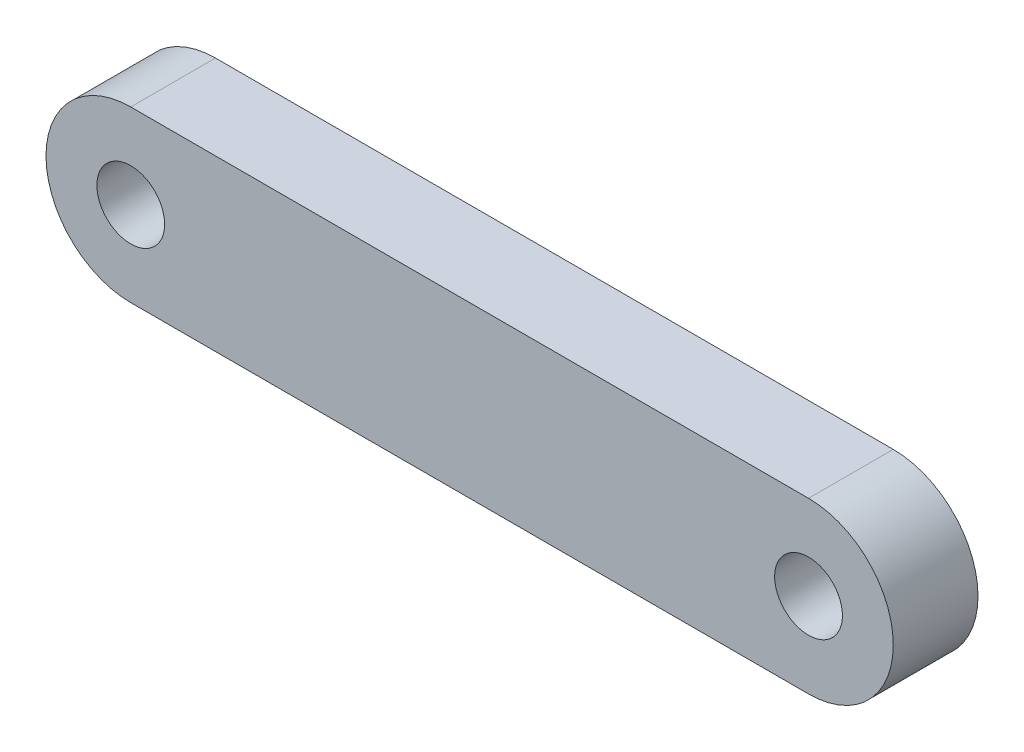
SolidWorks part; units mm, degrees
ref_plane "Alzado" through (0, 0, 0) normal (0, 0, 1) x (1, 0, 0)
ref_plane "Planta" through (0, 0, 0) normal (0, 1, 0) x (1, 0, 0)
ref_plane "Vista lateral" through (0, 0, 0) normal (1, 0, 0) x (0, 0, -1)
sketch "Croquis1" plane through (0, 0, 0) normal (0, 0, 1) x (1, 0, 0)
  line L1 (-16.7366, 3.1816) -> (23.2634, 3.1816)
  line L3 (-16.7366, -6.8184) -> (23.2634, -6.8184)
  arc A0 (-16.7366, 3.1816) -> (-16.7366, -6.8184) centre (-16.7366, -1.8184) ccw
  arc A1 (23.2634, -6.8184) -> (23.2634, 3.1816) centre (23.2634, -1.8184) ccw
  dimension "D1" = 40
  dimension "D2" = 5
  dimension "D3" = 5
extrude "Saliente-Extruir1" add sketch "Croquis1" along normal blind 5
sketch "Croquis2" plane through (0, 0, 5) normal (0, 0, 1) x (1, 0, 0)
  circle A0 centre (-16.7366, -1.8184) radius 2
  circle A1 centre (23.2634, -1.8184) radius 2
  dimension "D2" = 4
  dimension "D3" = 4
  dimension "D1" = 40
extrude "Cortar-Extruir1" cut sketch "Croquis2" against normal blind 5
